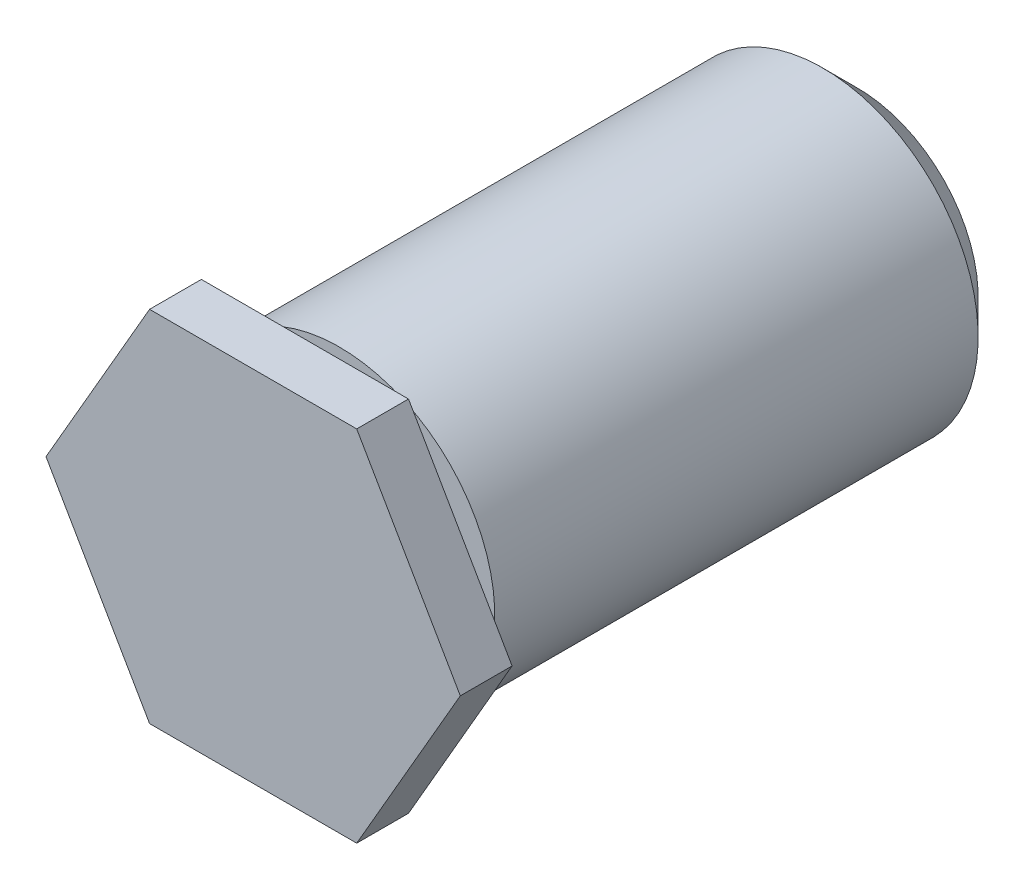
SolidWorks part; units mm, degrees
ref_plane "前视基准面" through (0, 0, 0) normal (0, 0, 1) x (1, 0, 0)
ref_plane "上视基准面" through (0, 0, 0) normal (0, 1, 0) x (1, 0, 0)
ref_plane "右视基准面" through (0, 0, 0) normal (1, 0, 0) x (0, 0, -1)
sketch "草图1" plane through (0, 0, 0) normal (0, 0, 1) x (1, 0, 0)
  line L2 (16, 0) -> (8, 13.8564)
  line L3 (8, 13.8564) -> (-8, 13.8564)
  line L4 (-8, 13.8564) -> (-16, 0)
  line L5 (-16, 0) -> (-8, -13.8564)
  line L6 (-8, -13.8564) -> (8, -13.8564)
  line L7 (8, -13.8564) -> (16, 0)
extrude "凸台-拉伸1" add sketch "草图1" along normal blind 3
sketch "草图2" plane through (0, 0, 0) normal (1, 0, 0) x (0, 0, -1)
  line L0 (0, 0) -> (0, 7)
  line L2 (0, 7) -> (2, 7)
  line L3 (2, 7) -> (2, 9)
  line L4 (2, 9) -> (30, 9)
  line L5 (32, 7) -> (32, 0)
  line L6 (32, 0) -> (0, 0)
  line L7 (30, 9) -> (32, 7)
  point P6 (32, 9)
revolve "旋转1" add sketch "草图2" angle 360 about L6
cosmetic thread "装饰螺纹线2" parameters "D2"=17
sketch "草图4" plane through (0, 0, 0) normal (0, 0, 1) x (1, 0, 0)
  line L2 (12, 0) -> (6, 10.3923)
  line L3 (6, 10.3923) -> (-6, 10.3923)
  line L4 (-6, 10.3923) -> (-12, 0)
  line L5 (-12, 0) -> (-6, -10.3923)
  line L6 (-6, -10.3923) -> (6, -10.3923)
  line L7 (6, -10.3923) -> (12, 0)
  line L8 (16, 0) -> (8, 13.8564)
  line L9 (8, 13.8564) -> (-8, 13.8564)
  line L10 (-8, 13.8564) -> (-16, 0)
  line L11 (-16, 0) -> (-8, -13.8564)
  line L12 (-8, -13.8564) -> (8, -13.8564)
  line L13 (8, -13.8564) -> (16, 0)
extrude "切除-拉伸1" cut sketch "草图4" along normal through all
